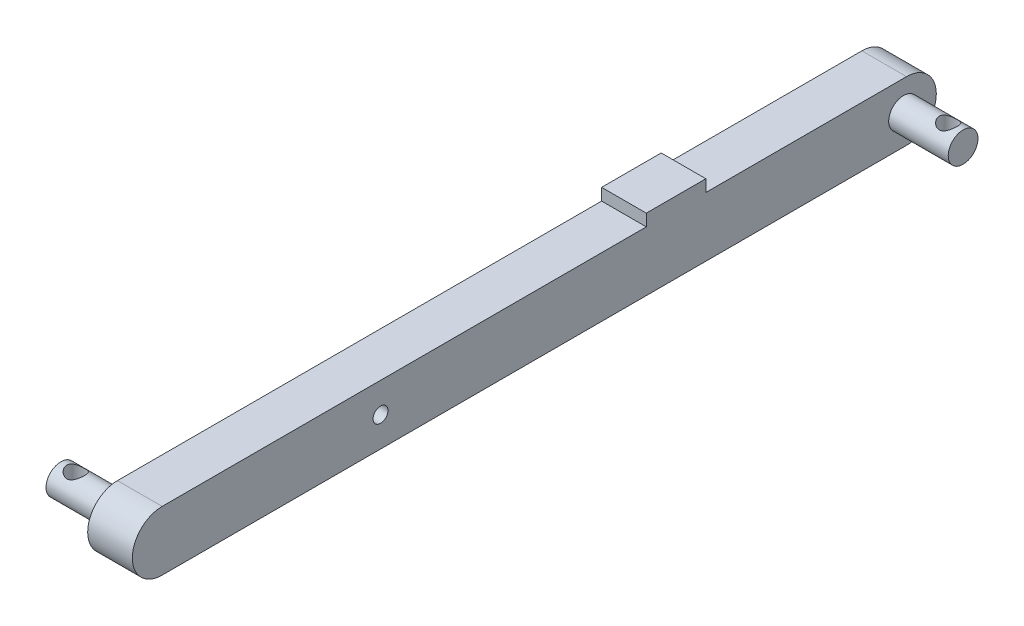
SolidWorks part; units mm, degrees
material "Oak"
ref_plane "Front Plane" through (0, 0, 0) normal (0, 0, 1) x (1, 0, 0)
ref_plane "Top Plane" through (0, 0, 0) normal (0, 1, 0) x (1, 0, 0)
ref_plane "Right Plane" through (0, 0, 0) normal (1, 0, 0) x (0, 0, -1)
sketch "Sketch2" plane through (0, 0, 0) normal (1, 0, 0) x (0, 0, -1)
  line L1 (-158.75, 12.7) -> (158.75, 12.7)
  line L3 (-158.75, -12.7) -> (158.75, -12.7)
  line L5 (-158.75, 12.7) -> (158.75, -12.7) construction
  line L6 (-158.75, -12.7) -> (158.75, 12.7) construction
  arc A0 (158.75, 12.7) -> (158.75, -12.7) centre (158.75, 0) cw
  arc A1 (-158.75, 12.7) -> (-158.75, -12.7) centre (-158.75, 0) ccw
  point P0 (0, 0)
  dimension "D1" = 25.4
  dimension "D2" = 317.5
extrude "Boss-Extrude1" add sketch "Sketch2" along normal mid plane 19.05
sketch "Sketch4" plane through (-9.525, 0, 0) normal (-1, 0, 0) x (0, 0, 1)
  line L0 (171.45, 0) -> (157.48, 0) construction
  circle A0 centre (157.48, 0) radius 6.35
  arc A1 (158.75, -12.7) -> (158.75, 12.7) centre (158.75, 0) ccw construction
  dimension "D2" = 12.7
  dimension "D1" = 13.97
extrude "Boss-Extrude2" add sketch "Sketch4" along normal blind 25.4
sketch "Sketch5" plane through (9.525, 0, 0) normal (1, 0, 0) x (0, 0, -1)
  line L0 (171.45, 0) -> (157.48, 0) construction
  circle A0 centre (157.48, 0) radius 6.35
  arc A1 (158.75, -12.7) -> (158.75, 12.7) centre (158.75, 0) ccw construction
  dimension "D2" = 12.7
  dimension "D1" = 13.97
extrude "Boss-Extrude3" add sketch "Sketch5" along normal blind 25.4
sketch "Sketch6" plane through (9.525, 0, 0) normal (1, 0, 0) x (0, 0, -1)
  line L0 (-171.45, 0) -> (-65.6082, 0) construction
  circle A0 centre (-65.6082, 0) radius 3.175
  arc A1 (-158.75, 12.7) -> (-158.75, -12.7) centre (-158.75, 0) ccw construction
  dimension "D1" = 6.35
  dimension "D2" = 105.8418
extrude "Cut-Extrude1" cut sketch "Sketch6" against normal up to surface (19.05 mm away) up to face at (-9.525, 0, 163.83)
sketch "Sketch10" plane through (0, 12.7, 0) normal (0, 1, 0) x (1, 0, 0)
  line L0 (9.525, 158.75) -> (9.525, -158.75) construction
  line L1 (-9.525, 47.752) -> (9.525, 47.752)
  line L2 (-9.525, 47.752) -> (-9.525, 73.152)
  line L3 (-9.525, 73.152) -> (9.525, 73.152)
  line L4 (9.525, 47.752) -> (9.525, 73.152)
  line L5 (-9.525, 47.752) -> (9.525, 73.152) construction
  line L6 (-9.525, 73.152) -> (9.525, 47.752) construction
  line L7 (9.525, 158.75) -> (-9.525, 158.75) construction
  line L8 (-9.525, 158.75) -> (-9.525, -158.75) construction
  point P0 (0, 60.452)
  dimension "D1" = 25.4
  dimension "D2" = 110.998
extrude "Boss-Extrude4" add sketch "Sketch10" along normal blind 5.08
sketch "Sketch11" plane through (0, 0, 0) normal (0, 1, 0) x (1, 0, 0)
  line L0 (-34.925, -157.48) -> (-9.525, -157.48) construction
  line L1 (-34.925, -151.13) -> (-34.925, -163.83) construction
  line L2 (-9.525, -151.13) -> (-9.525, -163.83) construction
  line L3 (9.525, 157.48) -> (34.925, 157.48) construction
  line L4 (9.525, 151.13) -> (9.525, 163.83) construction
  line L5 (34.925, 151.13) -> (34.925, 163.83) construction
  circle A0 centre (-28.575, -157.48) radius 3.81
  circle A1 centre (28.575, 157.48) radius 3.81
  dimension "D1" = 7.62
  dimension "D2" = 19.05
  dimension "D3" = 7.62
  dimension "D4" = 19.05
extrude "Cut-Extrude2" cut sketch "Sketch11" against normal mid plane 12.7
